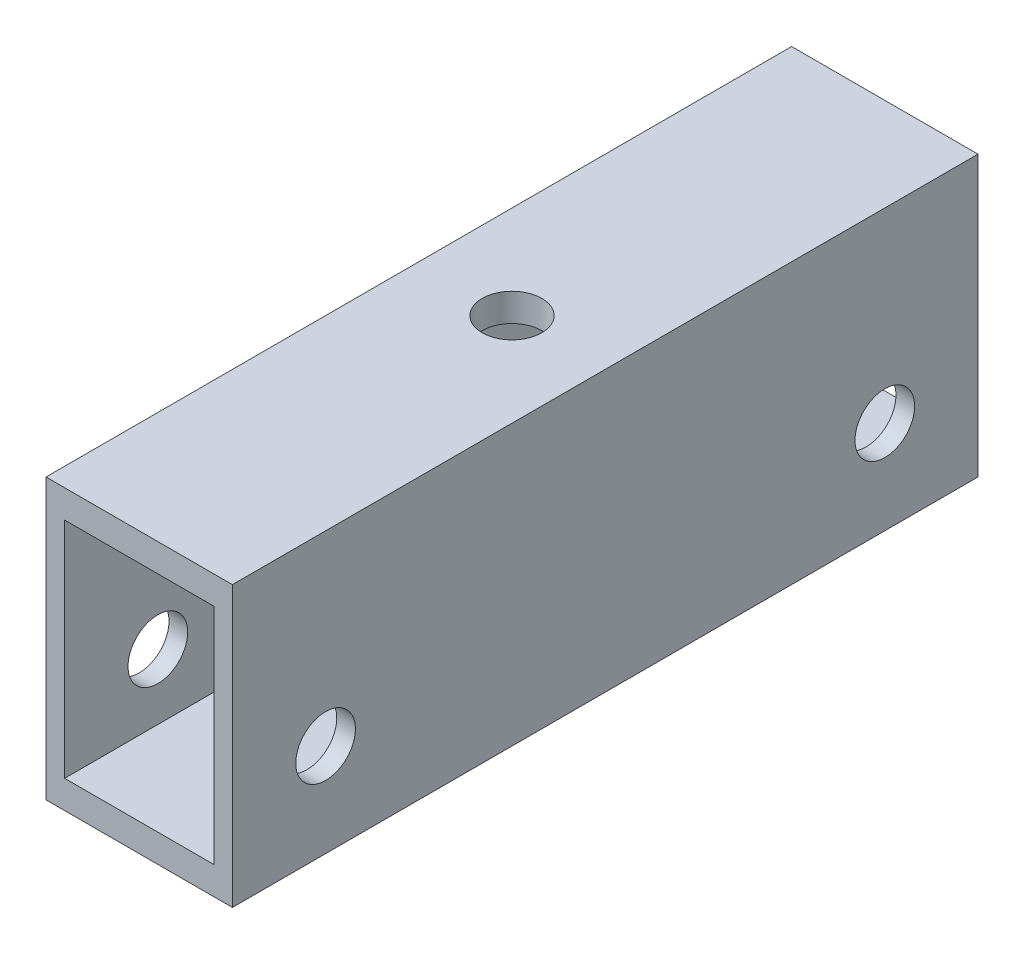
SolidWorks part; units mm, degrees
ref_plane "Front Plane" through (0, 0, 0) normal (0, 0, 1) x (1, 0, 0)
ref_plane "Top Plane" through (0, 0, 0) normal (0, 1, 0) x (1, 0, 0)
ref_plane "Right Plane" through (0, 0, 0) normal (1, 0, 0) x (0, 0, -1)
sketch "ｽｹｯﾁ1" plane through (0, 0, 0) normal (0, 0, 1) x (1, 0, 0)
  line L1 (5, -7.5) -> (-5, -7.5)
  line L2 (5, -7.5) -> (5, 7.5)
  line L3 (5, 7.5) -> (-5, 7.5)
  line L4 (-5, -7.5) -> (-5, 7.5)
  line L5 (5, -7.5) -> (-5, 7.5) construction
  line L6 (5, 7.5) -> (-5, -7.5) construction
  line L7 (4, -6) -> (-4, -6)
  line L8 (4, -6) -> (4, 6)
  line L9 (4, 6) -> (-4, 6)
  line L10 (-4, -6) -> (-4, 6)
  line L11 (4, -6) -> (-4, 6) construction
  line L12 (4, 6) -> (-4, -6) construction
  point P0 (0, 0)
  point P6 (0, 0)
  dimension "D1" = 10
  dimension "D2" = 15
  dimension "D3" = 1
extrude "ﾎﾞｽ - 押し出し1" add sketch "ｽｹｯﾁ1" along normal blind 40
sketch "ｽｹｯﾁ2" plane through (0, 7.5, 0) normal (0, 1, 0) x (1, 0, 0)
  line L0 (5, 0) -> (-5, 0) construction
  line L1 (5, -40) -> (5, 0) construction
  circle A0 centre (0, -20) radius 1.6
  dimension "D1" = 3.2
  dimension "D2" = 20
  dimension "D3" = 5
extrude "ｶｯﾄ - 押し出し1" cut sketch "ｽｹｯﾁ2" against normal through all
sketch "ｽｹｯﾁ3" plane through (5, 0, 0) normal (1, 0, 0) x (0, 0, -1)
  line L0 (-40, -7.5) -> (0, -7.5) construction
  line L1 (0, -7.5) -> (0, 7.5) construction
  circle A0 centre (-35, -2.5) radius 1.6
  circle A1 centre (-5, -2.5) radius 1.6
  dimension "D1" = 3.2
  dimension "D2" = 3.2
  dimension "D3" = 5
  dimension "D5" = 5
  dimension "D6" = 30
  dimension "D4" = 5
extrude "ｶｯﾄ - 押し出し2" cut sketch "ｽｹｯﾁ3" against normal through all
